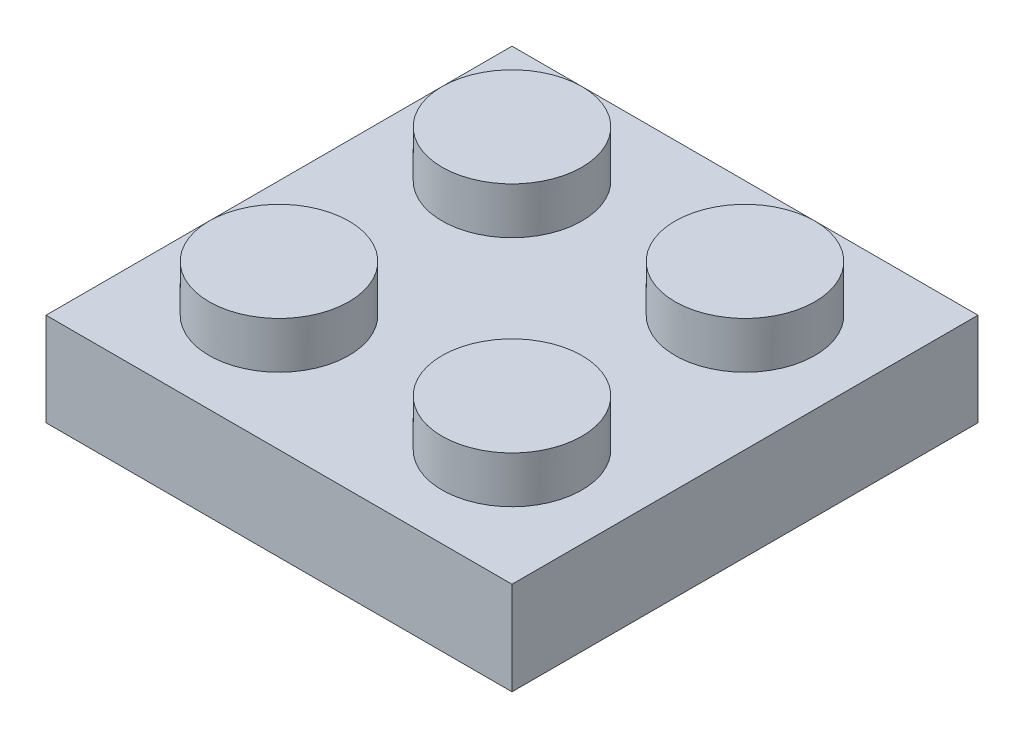
SolidWorks part; units mm, degrees
ref_plane "Front Plane" through (0, 0, 0) normal (0, 0, 1) x (1, 0, 0)
ref_plane "Top Plane" through (0, 0, 0) normal (0, 1, 0) x (1, 0, 0)
ref_plane "Right Plane" through (0, 0, 0) normal (1, 0, 0) x (0, 0, -1)
sketch "Sketch1" plane through (0, 0, 0) normal (0, 1, 0) x (1, 0, 0)
  line L1 (0, 0) -> (16, 0)
  line L2 (0, 0) -> (0, 16)
  line L3 (0, 16) -> (16, 16)
  line L4 (16, 0) -> (16, 16)
  dimension "D1" = 16
  dimension "D2" = 16
extrude "Boss-Extrude1" add sketch "Sketch1" along normal blind 3.2
sketch "Sketch2" plane through (0, 3.2, 0) normal (0, 1, 0) x (1, 0, 0)
  line L0 (8, 0) -> (8, 16) construction
  line L1 (0, 0) -> (16, 0) construction
  line L2 (16, 16) -> (0, 16) construction
  line L3 (16, 0) -> (16, 4) construction
  line L4 (16, 0) -> (16, 16) construction
  line L5 (16, 4) -> (12, 4) construction
  circle A0 centre (12, 4) radius 2.4
  dimension "D3" = 4.8
  dimension "D1" = 4
  dimension "D2" = 4
extrude "Boss-Extrude2" add sketch "Sketch2" along normal blind 1.6
pattern_linear "LPattern1" count 2 spacing 8 along (-1, 0, 0) count 4 spacing 8 along (0, 0, -1) of "Boss-Extrude2"
shell "Shell1" thickness 1.6
